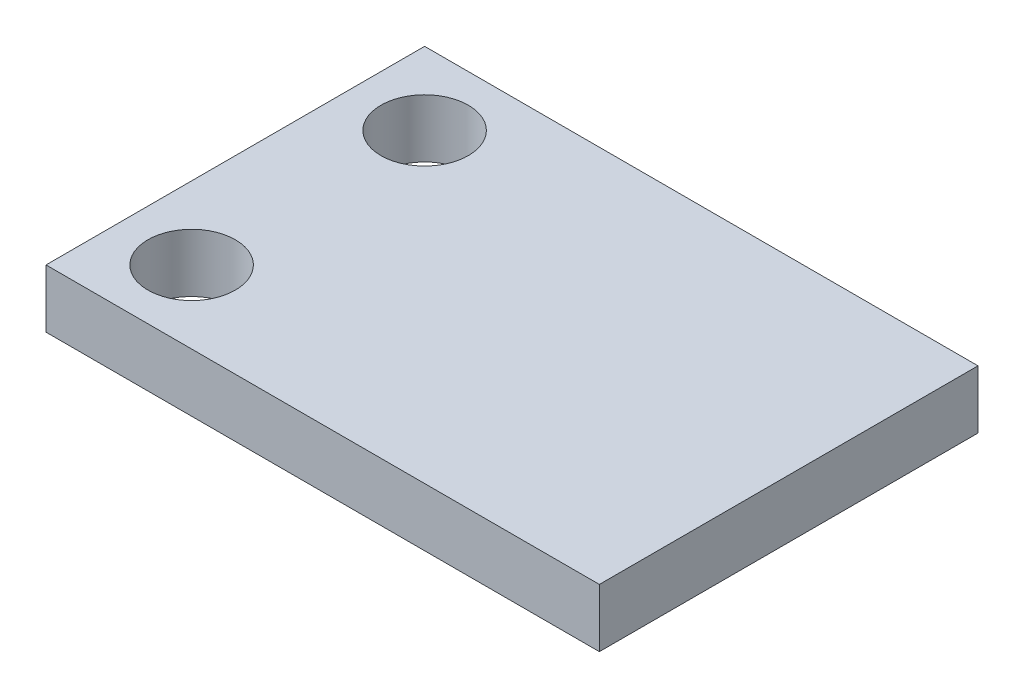
SolidWorks part; units mm, degrees
ref_plane "Front Plane" through (0, 0, 0) normal (0, 0, 1) x (1, 0, 0)
ref_plane "Top Plane" through (0, 0, 0) normal (0, 1, 0) x (1, 0, 0)
ref_plane "Right Plane" through (0, 0, 0) normal (1, 0, 0) x (0, 0, -1)
sketch "Sketch1" plane through (0, 0, 0) normal (0, 1, 0) x (1, 0, 0)
  line L0 (-9.5, 0) -> (9.5, 0) construction
  line L1 (-9.5, -6.5) -> (9.5, -6.5)
  line L2 (-9.5, -6.5) -> (-9.5, 6.5)
  line L3 (-9.5, 6.5) -> (9.5, 6.5)
  line L4 (9.5, -6.5) -> (9.5, 6.5)
  line L5 (-9.5, -6.5) -> (9.5, 6.5) construction
  line L6 (-9.5, 6.5) -> (9.5, -6.5) construction
  circle A0 centre (-7, 4) radius 1.5
  circle A1 centre (-7, -4) radius 1.5
  point P0 (0, 0)
  dimension "D3" = 3
  dimension "D1" = 13
  dimension "D2" = 19
  dimension "D4" = 2.5
  dimension "D5" = 2.5
extrude "Boss-Extrude1" add sketch "Sketch1" along normal blind 2
